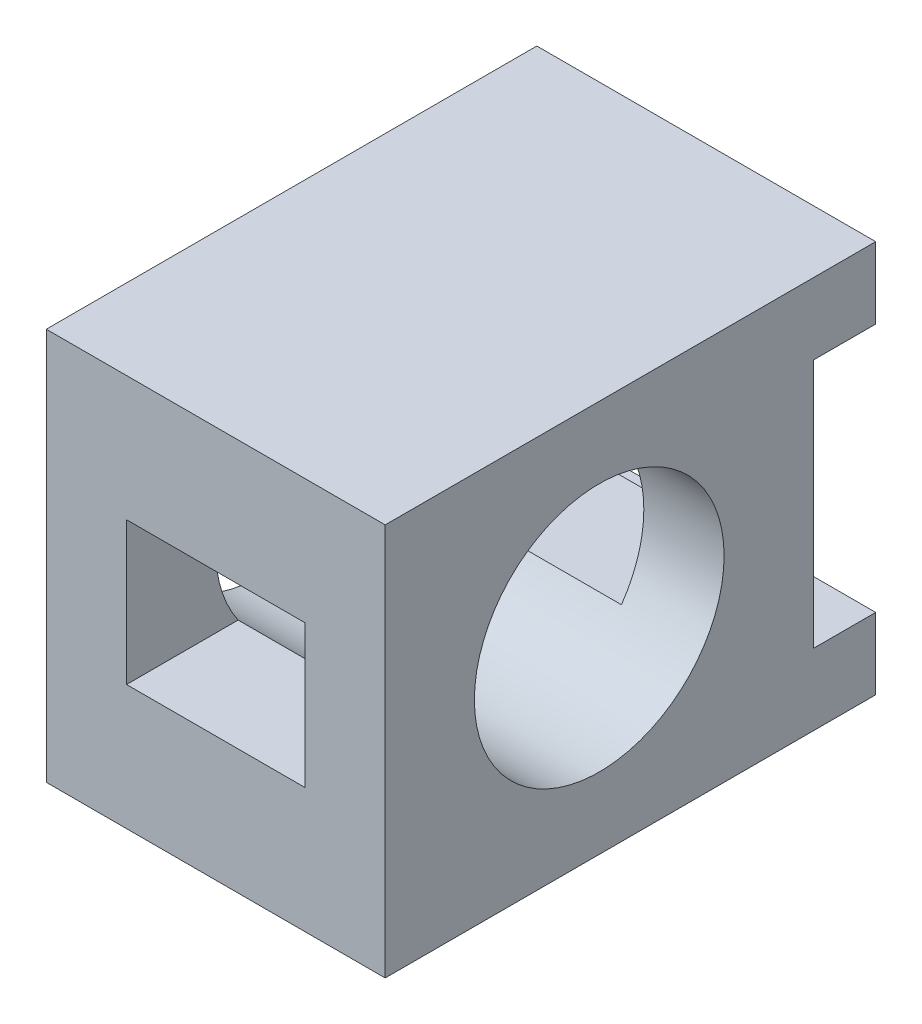
SolidWorks part; units mm, degrees
ref_plane "Front Plane" through (0, 0, 0) normal (0, 0, 1) x (1, 0, 0)
ref_plane "Top Plane" through (0, 0, 0) normal (0, 1, 0) x (1, 0, 0)
ref_plane "Right Plane" through (0, 0, 0) normal (1, 0, 0) x (0, 0, -1)
sketch "Sketch1" plane through (0, 0, 0) normal (0, 0, 1) x (1, 0, 0)
  line L1 (0, 0) -> (38, 0)
  line L2 (0, 0) -> (0, 44)
  line L3 (0, 44) -> (38, 44)
  line L4 (38, 0) -> (38, 44)
  dimension "D1" = 38
  dimension "D2" = 44
extrude "Boss-Extrude1" add sketch "Sketch1" along normal mid plane 55
sketch "Sketch2" plane through (0, 0, 27.5) normal (0, 0, 1) x (1, 0, 0)
  line L0 (0, 0) -> (38, 0) construction
  line L1 (9, 30) -> (29, 30)
  line L2 (9, 30) -> (9, 14)
  line L3 (9, 14) -> (29, 14)
  line L4 (29, 30) -> (29, 14)
  line L5 (38, 0) -> (38, 44) construction
  point P10 (19, 30)
  dimension "D1" = 16
  dimension "D2" = 20
  dimension "D3" = 30
  dimension "D4" = 9
extrude "Cut-Extrude1" cut sketch "Sketch2" against normal blind 55
sketch "Sketch3" plane through (38, 0, 0) normal (1, 0, 0) x (0, 0, -1)
  line L0 (-27.5, 0) -> (-27.5, 44) construction
  line L1 (-27.5, 0) -> (27.5, 0) construction
  circle A0 centre (-3.5, 22) radius 14
  dimension "D1" = 28
  dimension "D2" = 24
  dimension "D3" = 22
extrude "Cut-Extrude2" cut sketch "Sketch3" against normal blind 55
sketch "Sketch4" plane through (38, 0, 0) normal (1, 0, 0) x (0, 0, -1)
  line L0 (27.5, 36) -> (20.5, 36)
  line L1 (27.5, 0) -> (27.5, 44) construction
  line L2 (20.5, 36) -> (20.5, 8)
  line L3 (20.5, 8) -> (27.5, 8)
  line L4 (27.5, 36) -> (27.5, 8)
  line L6 (-27.5, 0) -> (27.5, 0) construction
  point P12 (20.5, 22)
  dimension "D1" = 28
  dimension "D2" = 7
  dimension "D3" = 8
extrude "Cut-Extrude3" cut sketch "Sketch4" against normal through all
